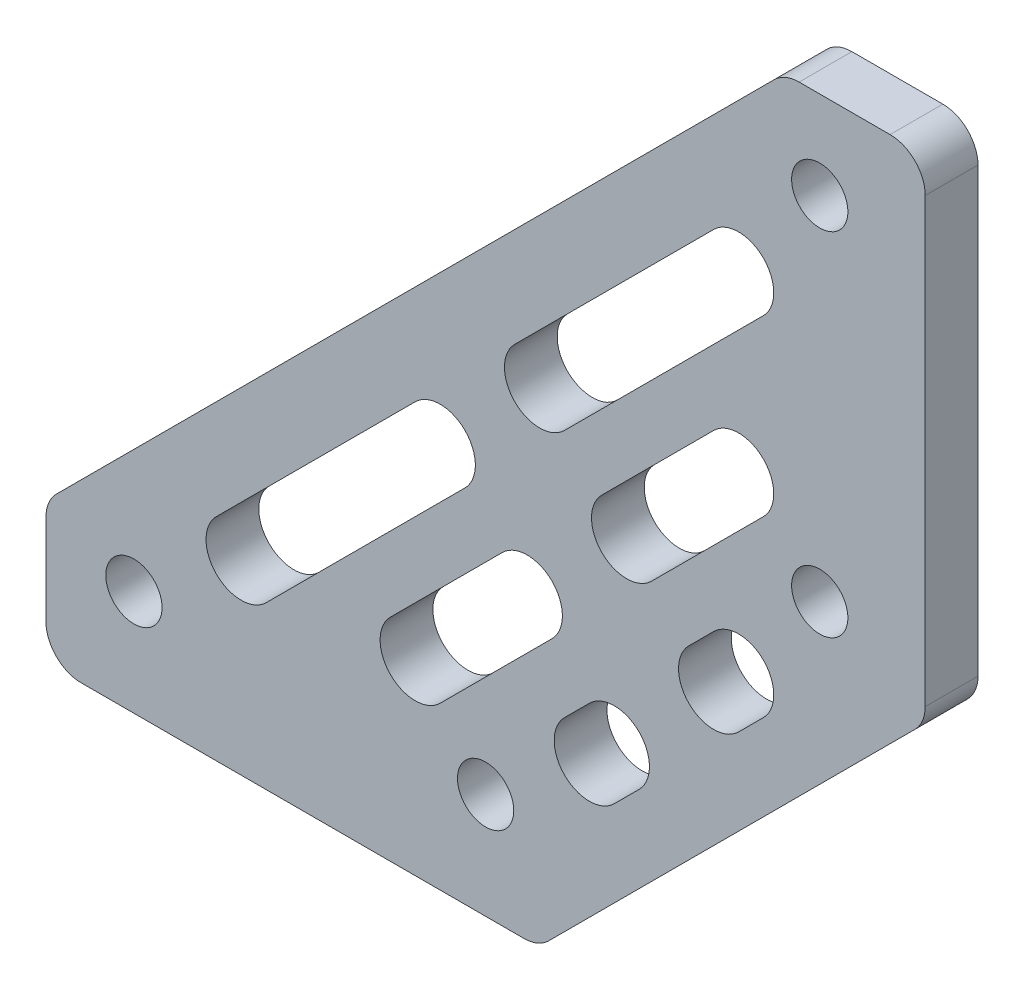
SolidWorks part; units mm, degrees
material "Thornel Mat VMA"
ref_plane "前视基准面" through (0, 0, 0) normal (0, 0, 1) x (1, 0, 0)
ref_plane "上视基准面" through (0, 0, 0) normal (0, 1, 0) x (1, 0, 0)
ref_plane "右视基准面" through (0, 0, 0) normal (1, 0, 0) x (0, 0, -1)
sketch "草图1" plane through (0, 0, 0) normal (0, 0, 1) x (1, 0, 0)
  line L0 (0, 0) -> (28, 0)
  line L1 (28, 0) -> (50, 22)
  line L2 (50, 22) -> (50, 50)
  line L3 (50, 50) -> (42, 50)
  line L4 (42, 50) -> (0, 8)
  line L5 (0, 8) -> (0, 0)
  line L6 (39, 11) -> (21, 29) construction
  circle A0 centre (5, 6) radius 1.6
  circle A1 centre (25, 6) radius 1.6
  circle A2 centre (44, 45) radius 1.6
  circle A3 centre (44, 25) radius 1.6
  dimension "D4" = 3.2
  dimension "D1" = 45
  dimension "D2" = 8
  dimension "D3" = 6
  dimension "D5" = 45
  dimension "D6" = 20
  dimension "D7" = 5
  dimension "D8" = 3
extrude "凸台-拉伸1" add sketch "草图1" along normal blind 3
fillet "圆角1" radius 2 6 edges at (28, 0, 1.5) (0, 0, 1.5) (0, 8, 1.5) (50, 22, 1.5) (50, 50, 1.5) (42, 50, 1.5)
sketch "草图2" plane through (0, 0, 3) normal (0, 0, 1) x (1, 0, 0)
  line L0 (11.1005, 10.6152) -> (22.4142, 21.9289) construction
  line L1 (9.6863, 12.0294) -> (21, 23.3431)
  line L2 (12.5147, 9.201) -> (23.8284, 20.5147)
  line L3 (41.4142, 49.4142) -> (0.5858, 8.5858) construction
  line L4 (21, 29) -> (39, 11) construction
  line L5 (28.5858, 0.5858) -> (49.4142, 21.4142) construction
  line L6 (27.364, 16.9792) -> (21, 10.6152) construction
  line L7 (28.7782, 15.565) -> (22.4142, 9.201)
  line L8 (25.9497, 18.3934) -> (19.5858, 12.0294)
  line L9 (22.4142, 21.9289) -> (27.364, 16.9792) construction
  line L10 (21, 10.6152) -> (11.1005, 10.6152) construction
  line L11 (30.8995, 10.6152) -> (32.3137, 12.0294) construction
  line L12 (29.4853, 12.0294) -> (30.8995, 13.4437)
  line L13 (32.3137, 9.201) -> (33.7279, 10.6152)
  line L14 (32.3137, 12.0294) -> (27.364, 16.9792) construction
  line L15 (39.3848, 38.8995) -> (28.0711, 27.5858) construction
  line L16 (37.9706, 40.3137) -> (26.6569, 29)
  line L17 (40.799, 37.4853) -> (29.4853, 26.1716)
  line L18 (33.0208, 22.636) -> (39.3848, 29) construction
  line L19 (34.435, 21.2218) -> (40.799, 27.5858)
  line L20 (31.6066, 24.0503) -> (37.9706, 30.4142)
  line L21 (39.3848, 19.1005) -> (37.9706, 17.6863) construction
  line L22 (37.9706, 20.5147) -> (36.5563, 19.1005)
  line L23 (40.799, 17.6863) -> (39.3848, 16.2721)
  arc A0 (9.6863, 12.0294) -> (12.5147, 9.201) centre (11.1005, 10.6152) ccw
  arc A1 (23.8284, 20.5147) -> (21, 23.3431) centre (22.4142, 21.9289) ccw
  arc A2 (28.7782, 15.565) -> (25.9497, 18.3934) centre (27.364, 16.9792) ccw
  arc A3 (19.5858, 12.0294) -> (22.4142, 9.201) centre (21, 10.6152) ccw
  arc A4 (29.4853, 12.0294) -> (32.3137, 9.201) centre (30.8995, 10.6152) ccw
  arc A5 (33.7279, 10.6152) -> (30.8995, 13.4437) centre (32.3137, 12.0294) ccw
  arc A6 (37.9706, 40.3137) -> (40.799, 37.4853) centre (39.3848, 38.8995) cw
  arc A7 (29.4853, 26.1716) -> (26.6569, 29) centre (28.0711, 27.5858) cw
  arc A8 (34.435, 21.2218) -> (31.6066, 24.0503) centre (33.0208, 22.636) cw
  arc A9 (37.9706, 30.4142) -> (40.799, 27.5858) centre (39.3848, 29) cw
  arc A10 (37.9706, 20.5147) -> (40.799, 17.6863) centre (39.3848, 19.1005) cw
  arc A11 (39.3848, 16.2721) -> (36.5563, 19.1005) centre (37.9706, 17.6863) cw
  point P2 (16.7574, 16.2721)
  point P15 (24.182, 13.7972)
  point P26 (31.6066, 11.3223)
  point P35 (33.7279, 33.2426)
  point P42 (36.2028, 25.818)
  point P49 (38.6777, 18.3934)
  dimension "D1" = 2
  dimension "D2" = 6
  dimension "D3" = 8
  dimension "D4" = 16
  dimension "D5" = 7
  dimension "D6" = 7
extrude "切除-拉伸1" cut sketch "草图2" against normal blind 10
